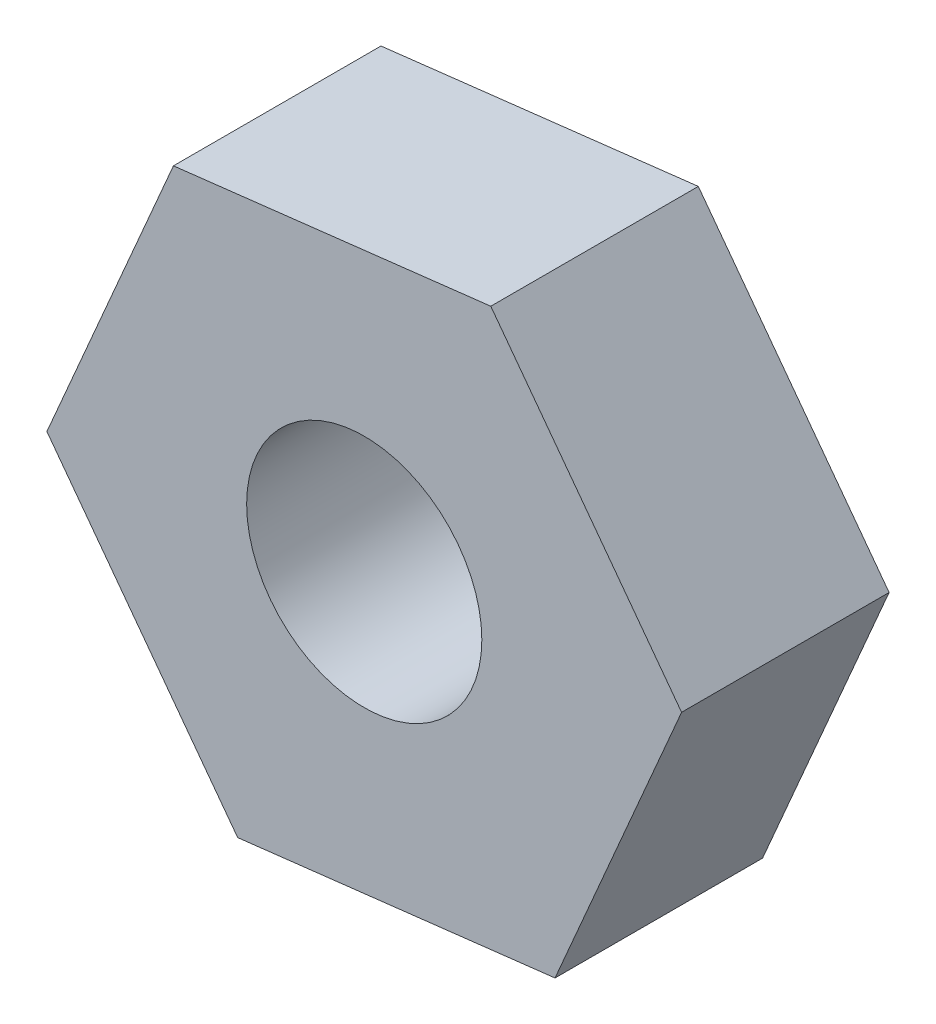
SolidWorks part; units mm, degrees
ref_plane "Front Plane" through (0, 0, 0) normal (0, 0, 1) x (1, 0, 0)
ref_plane "Top Plane" through (0, 0, 0) normal (0, 1, 0) x (1, 0, 0)
ref_plane "Right Plane" through (0, 0, 0) normal (1, 0, 0) x (0, 0, -1)
sketch "Sketch1" plane through (0, 0, 0) normal (0, 0, 1) x (1, 0, 0)
  line L1 (1.379, -1.8524) -> (2.2938, 0.2681)
  line L2 (2.2938, 0.2681) -> (0.9147, 2.1205)
  line L3 (0.9147, 2.1205) -> (-1.379, 1.8524)
  line L4 (-1.379, 1.8524) -> (-2.2938, -0.2681)
  line L5 (-2.2938, -0.2681) -> (-0.9147, -2.1205)
  line L6 (-0.9147, -2.1205) -> (1.379, -1.8524)
  circle A0 centre (0, 0) radius 2 construction
  circle A1 centre (0, 0) radius 0.85
  dimension "D2" = 1.7
  dimension "D1" = 4
extrude "Boss-Extrude1" add sketch "Sketch1" along normal blind 1.5
